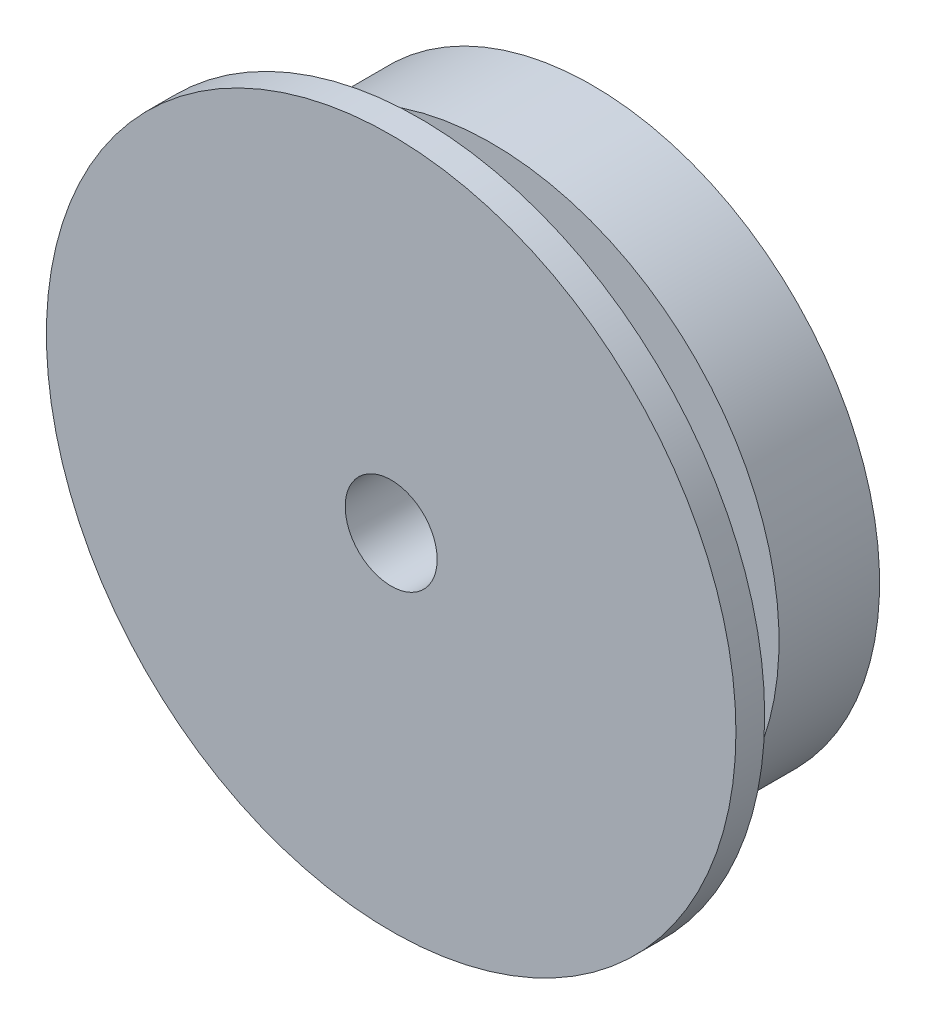
SolidWorks part; units mm, degrees
material "Resina de melamina"
ref_plane "Alzado" through (0, 0, 0) normal (0, 0, 1) x (1, 0, 0)
ref_plane "Planta" through (0, 0, 0) normal (0, 1, 0) x (1, 0, 0)
ref_plane "Vista lateral" through (0, 0, 0) normal (1, 0, 0) x (0, 0, -1)
sketch "Croquis1" plane through (0, 0, 0) normal (0, 0, 1) x (1, 0, 0)
  circle A0 centre (0, 0) radius 11
  circle A1 centre (0, 0) radius 25
  dimension "D1" = 50
  dimension "D2" = 22
extrude "Saliente-Extruir1" add sketch "Croquis1" along normal blind 19
ref_plane "Plano1" through (0, 0, 6) normal (0, 0, -1) x (-1, 0, 0)
sketch "Croquis3" plane through (0, 0, 6) normal (0, 0, -1) x (-1, 0, 0)
  circle A0 centre (0, 0) radius 11
  circle A1 centre (0, 0) radius 9.5
  dimension "D1" = 19
extrude "Saliente-Extruir2" add sketch "Croquis3" against normal through all
sketch "Croquis4" plane through (0, 0, 19) normal (0, 0, 1) x (1, 0, 0)
  circle A0 centre (0, 0) radius 11
  circle A1 centre (0, 0) radius 4
  dimension "D1" = 8
extrude "Saliente-Extruir3" add sketch "Croquis4" against normal blind 2
sketch "Croquis5" plane through (0, 0, 19) normal (0, 0, 1) x (1, 0, 0)
  circle A0 centre (0, 0) radius 25
  circle A1 centre (0, 0) radius 30
  dimension "D1" = 60
extrude "Saliente-Extruir4" add sketch "Croquis5" against normal blind 2.5
ref_plane "Plano2" through (0, 0, 14.25) normal (0, 0, -1) x (-1, 0, 0)
sketch "Croquis6" plane through (0, 0, 14.25) normal (0, 0, -1) x (-1, 0, 0)
  circle A1 centre (0, 0) radius 25
  circle A2 centre (0, 0) radius 19
  dimension "D1" = 38
extrude "Cortar-Extruir1" cut sketch "Croquis6" along normal blind 4
sketch "Croquis7" plane through (0, 0, 0) normal (0, 0, -1) x (-1, 0, 0)
  circle A0 centre (0, 0) radius 11
  circle A1 centre (0, 0) radius 4
extrude "Saliente-Extruir5" add sketch "Croquis7" against normal through all
sketch "Croquis8" plane through (0, 0, 0) normal (0, 0, -1) x (-1, 0, 0)
  circle A0 centre (0, 0) radius 4
  circle A1 centre (0, 0) radius 6.1
  dimension "D1" = 12.2
extrude "Saliente-Extruir6" add sketch "Croquis8" along normal blind 1.5
sketch "Croquis9" plane through (0, 0, 0) normal (0, 0, -1) x (-1, 0, 0)
  circle A0 centre (0, 0) radius 25
  circle A1 centre (0, 0) radius 15
  dimension "D1" = 30
extrude "Cortar-Extruir2" cut sketch "Croquis9" against normal blind 1.5
